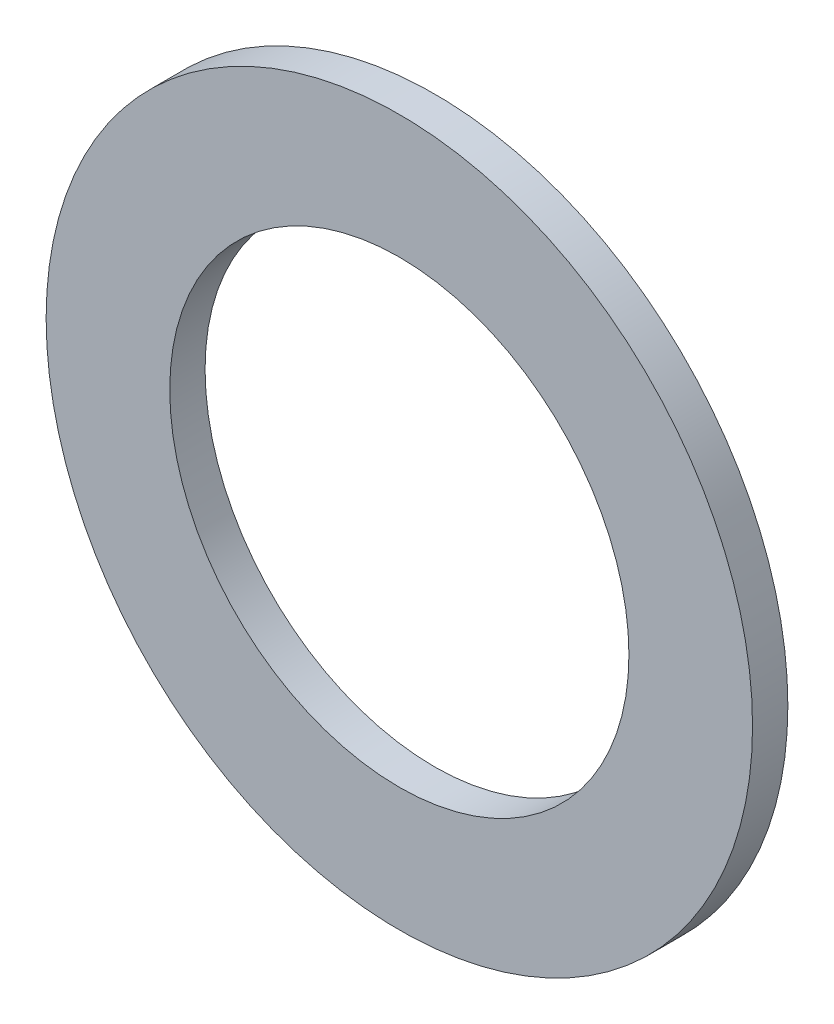
SolidWorks part; units mm, degrees
material "Латунь"
ref_plane "Спереди" through (0, 0, 0) normal (0, 0, 1) x (1, 0, 0)
ref_plane "Сверху" through (0, 0, 0) normal (0, 1, 0) x (1, 0, 0)
ref_plane "Справа" through (0, 0, 0) normal (1, 0, 0) x (0, 0, -1)
sketch "Эскиз1" plane through (0, 0, 0) normal (0, 0, 1) x (1, 0, 0)
  circle A0 centre (0, 0) radius 5
  circle A1 centre (0, 0) radius 3.25
  dimension "D1" = 6.5
  dimension "D2" = 10
extrude "Вытянуть1" add sketch "Эскиз1" along normal blind 0.5
